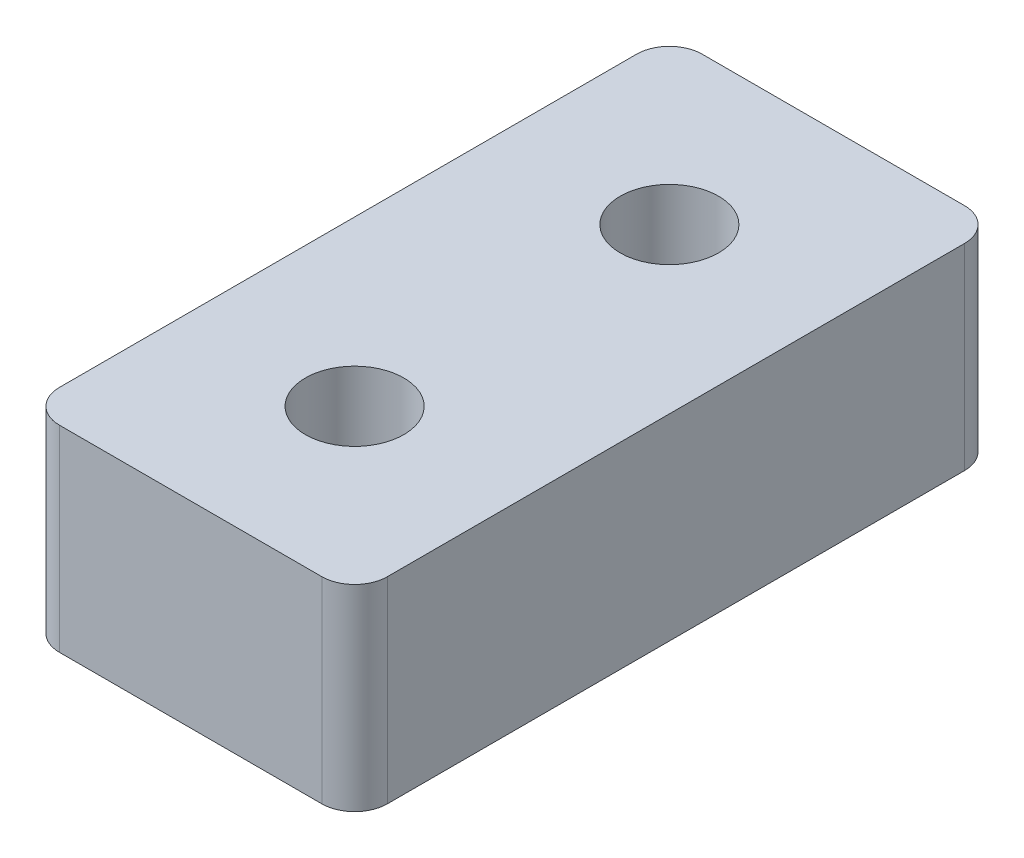
SolidWorks part; units mm, degrees
ref_plane "Front Plane" through (0, 0, 0) normal (0, 0, 1) x (1, 0, 0)
ref_plane "Top Plane" through (0, 0, 0) normal (0, 1, 0) x (1, 0, 0)
ref_plane "Right Plane" through (0, 0, 0) normal (1, 0, 0) x (0, 0, -1)
sketch "Sketch1" plane through (0, 0, 0) normal (0, 1, 0) x (1, 0, 0)
  line L0 (5, 14.6) -> (5, 5) construction
  line L1 (0, 0) -> (10, 0)
  line L2 (0, 0) -> (0, 19.6)
  line L3 (0, 19.6) -> (10, 19.6)
  line L4 (10, 0) -> (10, 19.6)
  line L5 (5, 5) -> (5, 0) construction
  line L6 (5, 9.8) -> (0, 9.8) construction
  circle A0 centre (5, 14.6) radius 1.5
  circle A1 centre (5, 5) radius 1.5
  dimension "D1" = 3
  dimension "D2" = 10
  dimension "D3" = 9.6
  dimension "D4" = 5
extrude "Boss-Extrude1" add sketch "Sketch1" along normal blind 6
fillet "Fillet1" radius 1 4 edges at (10, 3, -19.6) (10, 3, 0) (0, 3, 0) (0, 3, -19.6)
equation "\"housing_t\"= \"housing_t_glob@troublemaker.Assembly\""
equation "\"M3_d\"= \"M3_d_laser@troublemaker.Assembly\""
equation "\"D1@Sketch1\"=\"M3_d\""
equation "\"D1@Boss-Extrude1\"=\"housing_t\""
